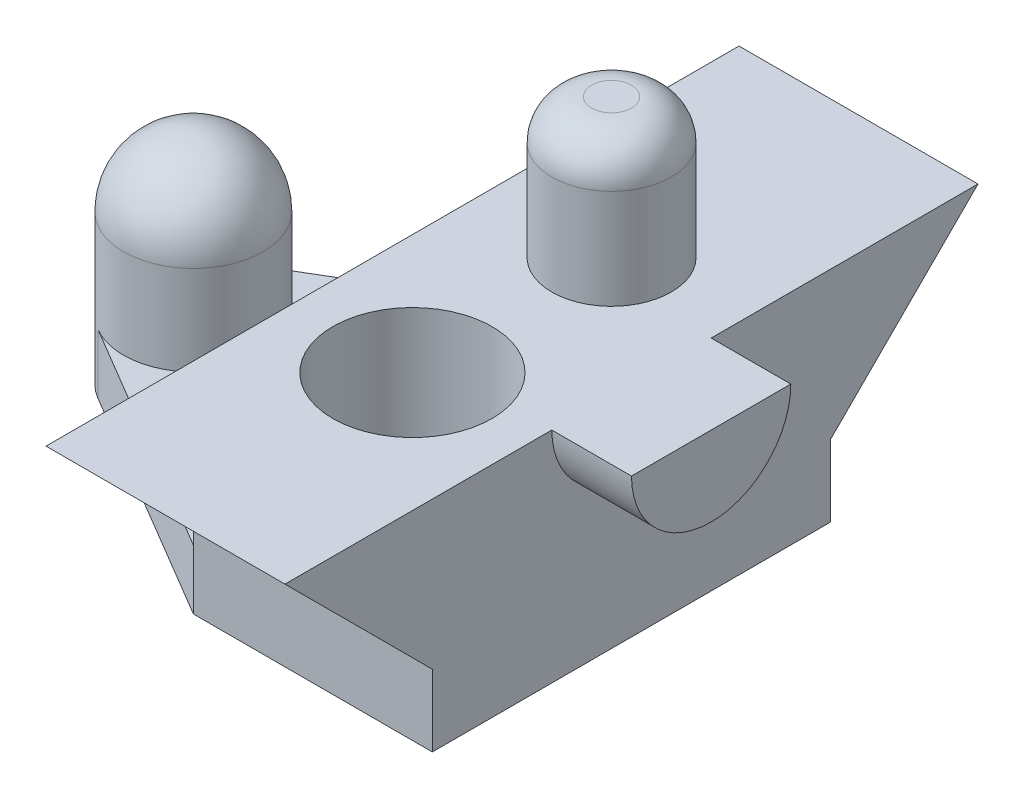
SolidWorks part; units mm, degrees
other "Markup1"
sketch "Sketch7" plane through (12, 7.5, 6.5) normal (0.0383, 0.9456, 0.3232) x (0.9932, -0.0006, -0.1161)
ref_plane "Front Plane" through (0, 0, 0) normal (0, 0, 1) x (1, 0, 0)
ref_plane "Top Plane" through (0, 0, 0) normal (0, 1, 0) x (1, 0, 0)
ref_plane "Right Plane" through (0, 0, 0) normal (1, 0, 0) x (0, 0, -1)
sketch "Sketch1" plane through (0, 0, 0) normal (0, 1, 0) x (1, 0, 0)
  line L0 (5, 5) -> (11, 5)
  line L1 (11, 5) -> (11, -5)
  line L2 (11, -5) -> (5, -5)
  line L3 (5, -5) -> (-0.8927, -1.5052)
  line L4 (5, 5) -> (-0.8927, 1.5052)
  arc A0 (-0.8927, 1.5052) -> (-0.8927, -1.5052) centre (0, 0) ccw
  point P11 (11, 0)
  dimension "D1" = 10
  dimension "D4" = 5
  dimension "D5" = 1.75
  dimension "D2" = 6
  dimension "D3" = 6
extrude "Boss-Extrude1" add sketch "Sketch1" against normal blind 1.5 contours L1 L2 L3 A0 L4 L0
sketch "Sketch2" plane through (0, 0, 0) normal (0, 1, 0) x (1, 0, 0)
  line L1 (5, 5) -> (11, 5)
  line L2 (5, 5) -> (5, -5)
  line L3 (5, -5) -> (11, -5)
  line L4 (11, 5) -> (11, -5)
  circle A0 centre (0, 0) radius 1.75
  dimension "D1" = 3.5
extrude "Boss-Extrude2" add sketch "Sketch2" along normal blind 4
sketch "Sketch3" plane through (0, 4, 0) normal (0, 1, 0) x (1, 0, 0)
  line L0 (5, 5) -> (11, 5)
  line L4 (-55, 0) -> (55, 0) construction
  line L6 (5, -5) -> (11, -5)
  line L7 (5, 5) -> (5, 8.25)
  line L8 (6.25, 9.5) -> (9.75, 9.5)
  line L9 (11, 8.25) -> (11, 5)
  line L10 (11, -8.25) -> (11, -5)
  line L11 (6.25, -9.5) -> (9.75, -9.5)
  line L12 (5, -5) -> (5, -8.25)
  arc A4 (5, 8.25) -> (6.25, 9.5) centre (6.25, 8.25) cw
  arc A5 (11, 8.25) -> (9.75, 9.5) centre (9.75, 8.25) ccw
  arc A6 (11, -8.25) -> (9.75, -9.5) centre (9.75, -8.25) cw
  arc A7 (5, -8.25) -> (6.25, -9.5) centre (6.25, -8.25) ccw
  dimension "D2" = 1.25
  dimension "D1" = 4.5
extrude "Boss-Extrude3" [suppressed] add sketch "Sketch3" against normal blind 2.25
fillet "Fillet1" radius 1.75 1 edges at (0, 4, 1.75)
sketch "Sketch4" plane through (0, 4, 0) normal (0, 1, 0) x (1, 0, 0)
  line L0 (5, 5) -> (5, -5) construction
  circle A0 centre (8, 2.5) radius 1.5
  dimension "D1" = 3
  dimension "D2" = 3
  dimension "D3" = 2.5
extrude "Boss-Extrude4" add sketch "Sketch4" along normal blind 3.5
fillet "Fillet2" radius 1 1 edges at (8, 7.5, -1)
sketch "Sketch5" plane through (0, 4, 0) normal (0, 1, 0) x (1, 0, 0)
  line L0 (5, 5) -> (5, -5) construction
  circle A0 centre (8, -2.5) radius 2
  dimension "D1" = 4
  dimension "D2" = 2.5
  dimension "D3" = 3
extrude "Cut-Extrude1" cut sketch "Sketch5" against normal blind 3.75
sketch "Sketch6" plane through (11, 0, 0) normal (1, 0, 0) x (0, 0, -1)
  line L0 (-5, 4) -> (5, 4) construction
  line L1 (-2, 4) -> (2, 4)
  arc A0 (-2, 4) -> (2, 4) centre (0, 4) ccw
  dimension "D1" = 4
extrude "Boss-Extrude5" add sketch "Sketch6" along normal blind 2
sketch "Sketch9" plane through (11, 0, 0) normal (1, 0, 0) x (0, 0, -1)
  line L0 (-5, 4) -> (-8.7, 4)
  line L1 (-8.7, 4) -> (-5, 0.3)
  line L2 (-5, 0.3) -> (-5, 4)
  line L3 (-5, -1.5) -> (-5, 4) construction
  line L4 (0, 4.95) -> (0, -4.95) construction
  line L5 (5, 0.3) -> (5, 4)
  line L6 (8.7, 4) -> (5, 0.3)
  line L7 (5, 4) -> (8.7, 4)
  dimension "D1" = 45
  dimension "D2" = 3.7
extrude "Boss-Extrude6" add sketch "Sketch9" against normal blind 6
